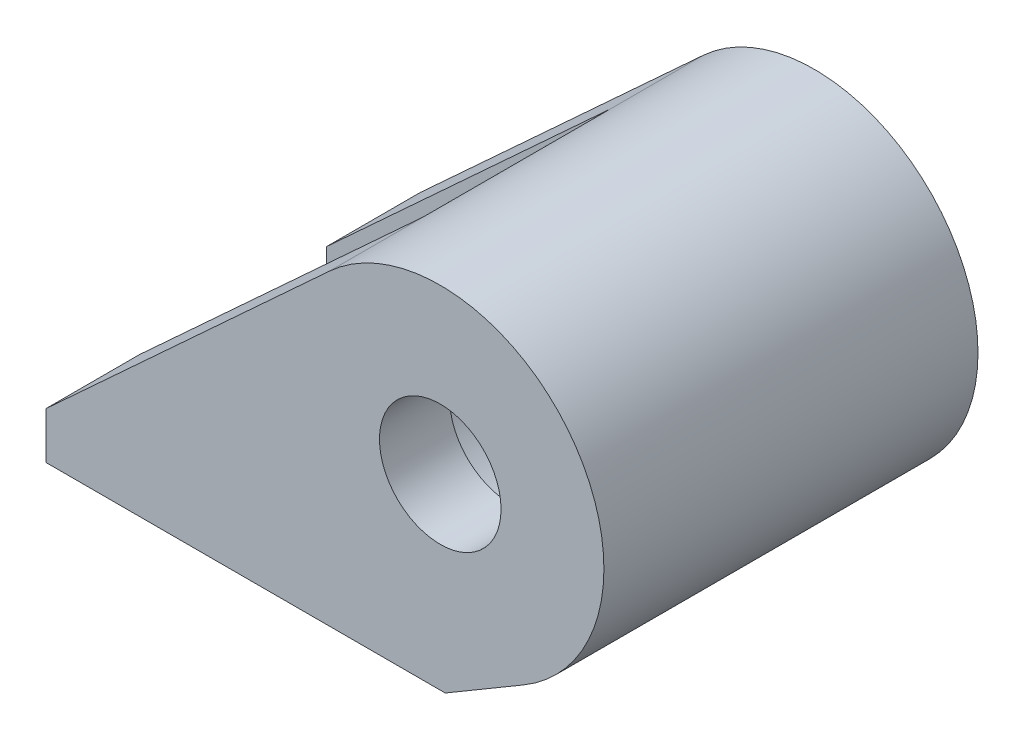
SolidWorks part; units mm, degrees
ref_plane "Спереди" through (0, 0, 0) normal (0, 0, 1) x (1, 0, 0)
ref_plane "Сверху" through (0, 0, 0) normal (0, 1, 0) x (1, 0, 0)
ref_plane "Справа" through (0, 0, 0) normal (1, 0, 0) x (0, 0, -1)
sketch "Эскиз1" plane through (0, 0, 0) normal (0, 0, 1) x (1, 0, 0)
  line L0 (0, 35) -> (-84.5144, 35) construction
  line L1 (0, 0) -> (35, 0) construction
  line L2 (35, 0) -> (35, -40) construction
  line L3 (35, -40) -> (-84.3144, -40) construction
  line L4 (-84.3144, -40) -> (-84.3144, -30) construction
  line L5 (-84.3144, -30) -> (-23.6946, 25.7598)
  line L6 (-84.3144, -30) -> (-84.3144, -40)
  line L7 (-84.3144, -40) -> (1.0606, -40)
  line L8 (0, 0) -> (0, -46.2136) construction
  line L9 (1.0606, -40) -> (17.7692, -30.1538)
  arc A0 (17.7692, -30.1538) -> (-23.6946, 25.7598) centre (0, 0) ccw
  dimension "D1" = 40
  dimension "D2" = 70
  dimension "D3" = 1.0606
  dimension "D4" = 10
  dimension "D5" = 23.6946
extrude "Бобышка-Вытянуть1" add sketch "Эскиз1" along normal blind 80
sketch "Эскиз2" plane through (0, 0, 0) normal (0, 0, 1) x (1, 0, 0)
  circle A0 centre (0, 0) radius 13
  dimension "D1" = 26
extrude "Вырез-Вытянуть2" cut sketch "Эскиз2" along normal blind 15
sketch "Эскиз4" plane through (0, 0, 80) normal (0, 0, 1) x (1, 0, 0)
  circle A0 centre (0, 0) radius 13
  dimension "D1" = 26
extrude "Вырез-Вытянуть3" cut sketch "Эскиз4" against normal blind 15
sketch "Эскиз5" plane through (0, 0, 0) normal (0, 1, 0) x (1, 0, 0)
  line L0 (-84.3144, 0) -> (-84.3144, -80) construction
  line L1 (-84.3144, -80) -> (-23.6946, -80) construction
  line L2 (-23.6946, -80) -> (-23.6946, 0) construction
  line L3 (-23.6946, 0) -> (-84.3144, 0) construction
  line L4 (-84.3144, 0) -> (-84.3144, -20) construction
  line L5 (-84.3144, -20) -> (-64.3144, -20) construction
  line L6 (-64.3144, -20) -> (-64.3144, -60) construction
  line L7 (-64.3144, -60) -> (-84.3144, -60) construction
  line L9 (-84.3144, -20) -> (-64.3144, -20)
  line L10 (-84.3144, -20) -> (-84.3144, -60)
  line L11 (-84.3144, -60) -> (-64.3144, -60)
  line L12 (-64.3144, -20) -> (-64.3144, -60)
  dimension "D1" = 64.3144
  dimension "D2" = 60
extrude "Вырез-Вытянуть4" cut sketch "Эскиз5" against normal through all both and the other way through all
sketch "Эскиз6" plane through (0, 0, 0) normal (0, 1, 0) x (1, 0, 0)
  line L1 (-84.3144, -80) -> (-23.6946, -80) construction
  line L2 (-23.6946, -80) -> (-23.6946, 0) construction
  line L3 (35, 0) -> (-23.6946, 0) construction
  line L4 (-23.6946, -80) -> (-23.6946, 0) construction
  line L5 (-23.6946, 0) -> (-84.3144, 0) construction
  line L9 (-55, -25) -> (-84.3144, -25)
  line L10 (-84.3144, -25) -> (-84.3144, -55)
  line L12 (-84.3144, -55) -> (-55, -55)
  arc A2 (-55, -55) -> (-55, -25) centre (-55, -40) ccw
  dimension "D1" = 15
  dimension "D2" = 55
  dimension "D3" = 40
extrude "Вырез-Вытянуть6" cut sketch "Эскиз6" against normal blind 24 and the other way through all
sketch "Эскиз9" plane through (0, -24, 0) normal (0, 1, 0) x (1, 0, 0)
  line L0 (-55, -48) -> (-92.7334, -48)
  line L1 (-92.7334, -48) -> (-92.7334, -32)
  line L2 (-92.7334, -32) -> (-55, -32)
  line L3 (-64.3144, -25) -> (-64.3144, -55) construction
  arc A0 (-55, -48) -> (-55, -32) centre (-55, -40) ccw
  dimension "D1" = 8
  dimension "D2" = 28.419
extrude "Вырез-Вытянуть7" cut sketch "Эскиз9" against normal through all
sketch "Эскиз10" plane through (0, 0, 0) normal (0, 1, 0) x (1, 0, 0)
  line L1 (-64.3144, -20) -> (-34.3144, -20)
  line L2 (-64.3144, -20) -> (-64.3144, -60)
  line L3 (-64.3144, -60) -> (-34.3144, -60)
  line L4 (-34.3144, -20) -> (-34.3144, -60)
  dimension "D1" = 34.3144
  dimension "D2" = 60
extrude "Вырез-Вытянуть8" cut sketch "Эскиз10" against normal blind 24 and the other way blind 32
sketch "Эскиз11" plane through (0, -24, 0) normal (0, 1, 0) x (1, 0, 0)
  line L0 (-34.3144, -60) -> (-34.3144, -20) construction
  line L1 (-55, -25) -> (-81.861, -25)
  line L3 (-55, -55) -> (-81.861, -55)
  line L4 (-81.861, -25) -> (-81.861, -55)
  arc A0 (-55, -55) -> (-55, -25) centre (-55, -40) ccw
  dimension "D1" = 15
  dimension "D2" = 47.5466
extrude "Вырез-Вытянуть9" cut sketch "Эскиз11" against normal blind 6
sketch "Эскиз12" plane through (0, 0, 0) normal (0, 0, 1) x (1, 0, 0)
  line L0 (-35, 0) -> (-35, -24)
  line L1 (-52.9502, 0) -> (37.7357, 0) construction
  line L2 (-35, -24) -> (-25.4755, -24)
  arc A0 (-25.4755, -24) -> (-35, 0) centre (0, 0) ccw
  dimension "D1" = 35
  dimension "D2" = 25.4755
sketch "Эскиз13" plane through (0, -24, 0) normal (0, 1, 0) x (1, 0, 0)
  line L0 (-23.6946, -80) -> (-23.6946, 0) construction
  line L1 (-34.3144, -20) -> (-23.6946, -20)
  line L2 (-34.3144, -20) -> (-34.3144, -60)
  line L3 (-34.3144, -60) -> (-23.6946, -60)
  line L4 (-23.6946, -20) -> (-23.6946, -60)
  line L5 (-34.3144, -60) -> (-34.3144, -20) construction
  dimension "D1" = 40
extrude "Вырез-Вытянуть10" cut sketch "Эскиз13" along normal blind 71
extrude "Бобышка-Вытянуть3" add sketch "Эскиз12" along normal blind 60
fillet "Скругление1" radius 3 1 edges at (-35, -24, 40)
sketch "Эскиз14" plane through (0, 0, 65) normal (0, 0, 1) x (1, 0, 0)
  circle A2 centre (0, 0) radius 25
  circle A3 centre (0, 0) radius 13 construction
  dimension "D1" = 50
extrude "Вырез-Вытянуть11" cut sketch "Эскиз14" against normal blind 50
sketch "Эскиз16" plane through (0, 0, 80) normal (0, 0, 1) x (1, 0, 0)
  circle A0 centre (0, 0) radius 13
extrude "Вырез-Вытянуть12" cut sketch "Эскиз16" against normal blind 95
sketch3d "Трехмерный эскиз1" plane through (0, 0, 0) normal (0, 0, 1) x (1, 0, 0)
  dimension "D1" = 15
sketch "Эскиз17" plane through (0, 15, 0) normal (0, 1, 0) x (1, 0, 0)
  line L0 (-91.3391, 0) -> (90.1025, 0) construction
  line L1 (0.6856, -65) -> (-4.3144, -65) construction
  line L2 (0.6856, -65) -> (5.6856, -65) construction
  line L3 (0.6856, -80) -> (0.6856, -65) construction
  line L4 (-84.3144, 0) -> (-84.3144, -80) construction
  line L5 (-84.3144, -80) -> (0.6856, -80) construction
  line L7 (-4.3144, -65) -> (5.6856, -65)
  line L8 (-4.3144, -65) -> (-4.3144, -15)
  line L9 (-4.3144, -15) -> (5.6856, -15)
  line L10 (5.6856, -65) -> (5.6856, -15)
  dimension "D1" = 0.6856
  dimension "D2" = 5.6856
  dimension "D3" = 15
  dimension "D4" = 65
extrude "Бобышка-Вытянуть4" add sketch "Эскиз17" along normal blind 16
sketch3d "Трехмерный эскиз2" plane through (0, 0, 0) normal (0, 0, 1) x (1, 0, 0)
  dimension "D1" = 15
sketch "Эскиз20" plane through (0, -15, 0) normal (0, 1, 0) x (1, 0, 0)
  line L0 (-84.3144, -80) -> (0.6856, -80) construction
  line L1 (-23.6946, -80) -> (35, -80) construction
  line L2 (0.6856, -80) -> (0.6856, -65) construction
  line L3 (0.6856, -65) -> (-4.3144, -65) construction
  line L4 (0.6856, -65) -> (5.6856, -65) construction
  line L6 (-4.3144, -65) -> (5.6856, -65)
  line L7 (-4.3144, -65) -> (-4.3144, -15)
  line L8 (-4.3144, -15) -> (5.6856, -15)
  line L9 (5.6856, -65) -> (5.6856, -15)
  dimension "D1" = 0.6856
  dimension "D2" = 5.6856
  dimension "D3" = 15
  dimension "D4" = 65
extrude "Бобышка-Вытянуть5" add sketch "Эскиз20" against normal blind 20
